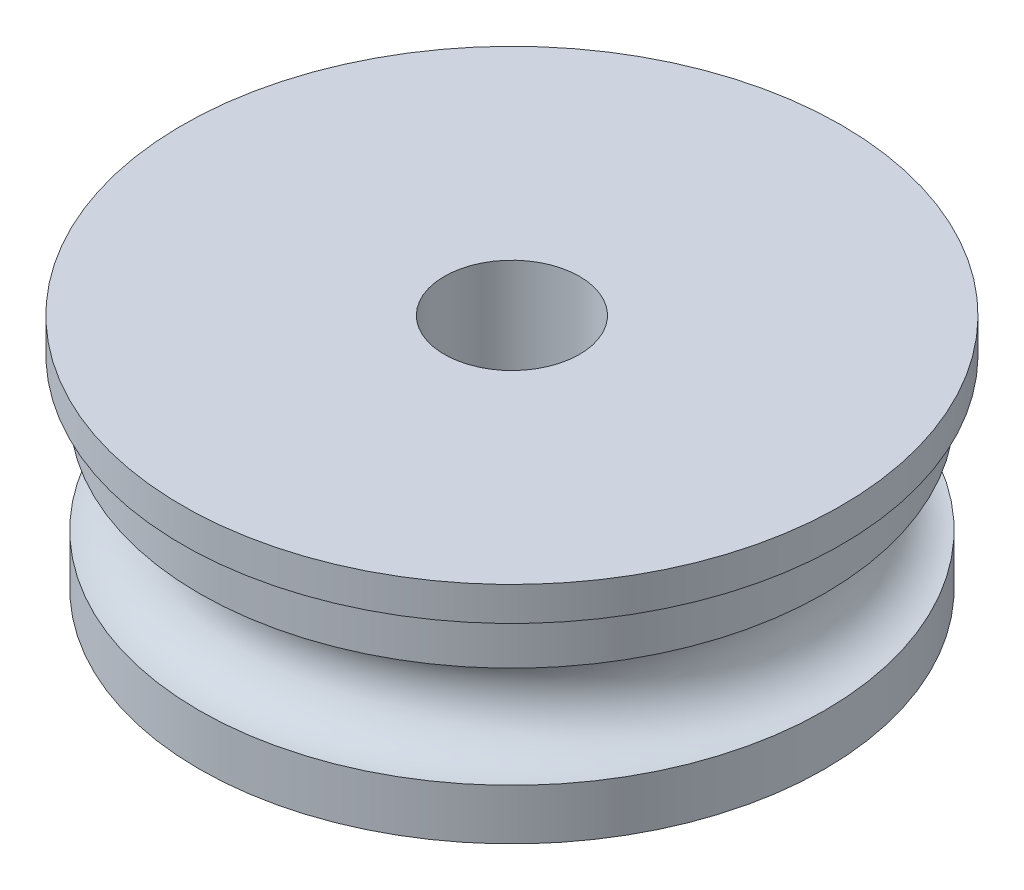
SolidWorks part; units mm, degrees
ref_plane "Front Plane" through (0, 0, 0) normal (0, 0, 1) x (1, 0, 0)
ref_plane "Top Plane" through (0, 0, 0) normal (0, 1, 0) x (1, 0, 0)
ref_plane "Right Plane" through (0, 0, 0) normal (1, 0, 0) x (0, 0, -1)
sketch "Sketch3" plane through (0, 0, 0) normal (0, 0, 1) x (1, 0, 0)
  line L0 (2, 0) -> (2, 4)
  line L1 (2, 4) -> (9.75, 4)
  line L2 (9.75, 4) -> (9.75, 3)
  line L3 (9.75, 3) -> (9.25, 3)
  line L4 (9.25, 3) -> (9.25, 1.5)
  line L5 (9.25, -3) -> (6, -3)
  line L6 (6, -3) -> (6, 0)
  line L7 (6, 0) -> (2, 0)
  line L8 (0, 0) -> (0, 4.9724) construction
  line L9 (0, 0) -> (0, -9.8079) construction
  line L10 (9.25, -1.5) -> (9.25, -3)
  arc A0 (9.25, 1.5) -> (9.25, -1.5) centre (9.25, 0) ccw
  dimension "D8" = 3
  dimension "D1" = 2
  dimension "D2" = 1
  dimension "D3" = 9.75
  dimension "D4" = 3
  dimension "D5" = 6
  dimension "D6" = 6
  dimension "D7" = 9.25
revolve "Revolve2" add sketch "Sketch3" angle 360 about L8
